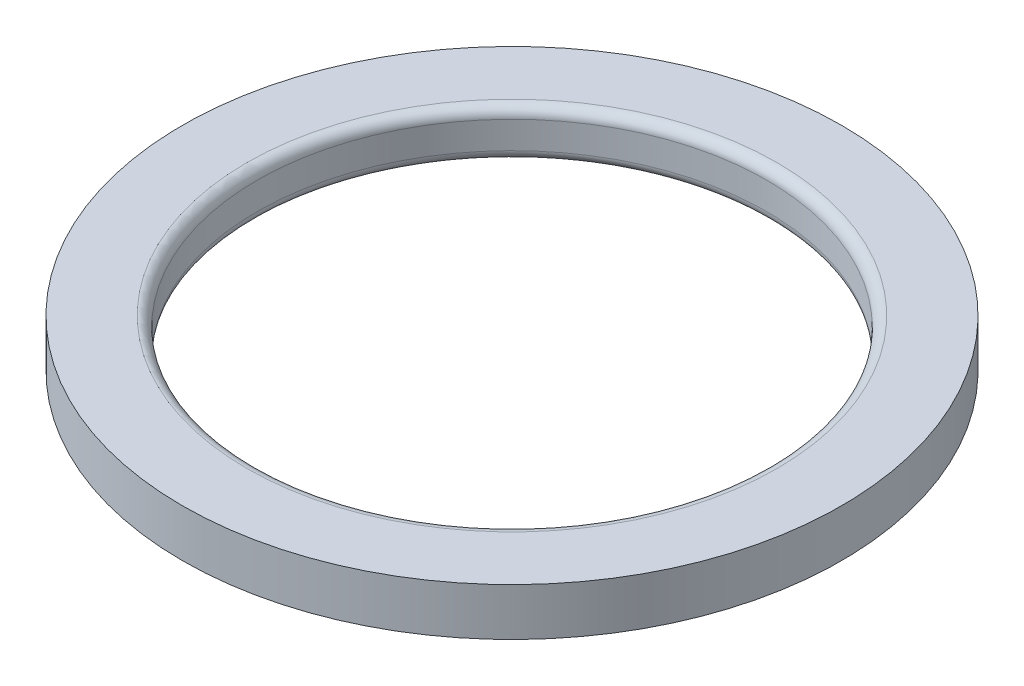
SolidWorks part; units mm, degrees
ref_plane "Front Plane" through (0, 0, 0) normal (0, 0, 1) x (1, 0, 0)
ref_plane "Top Plane" through (0, 0, 0) normal (0, 1, 0) x (1, 0, 0)
ref_plane "Right Plane" through (0, 0, 0) normal (1, 0, 0) x (0, 0, -1)
sketch "Sketch1" plane through (0, 0, 0) normal (0, 1, 0) x (1, 0, 0)
  circle A0 centre (0, 0) radius 7.5
  circle A1 centre (0, 0) radius 9.7
  dimension "D1" = 15
  dimension "D2" = 2.2
extrude "Boss-Extrude1" add sketch "Sketch1" along normal blind 1.4
fillet "Fillet1" radius 0.3 2 edges at (0, 0, 7.5) (0, 1.4, 7.5)
